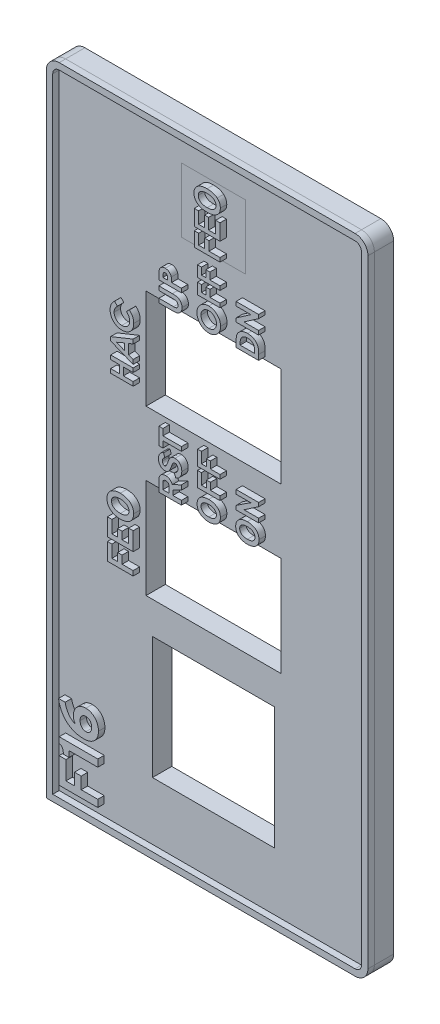
SolidWorks part; units mm, degrees
ref_plane "Front Plane" through (0, 0, 0) normal (1, 0, 0) x (0, 1, 0)
ref_plane "Top Plane" through (0, 0, 0) normal (0, 0, 1) x (0, 1, 0)
ref_plane "Right Plane" through (0, 0, 0) normal (0, 1, 0) x (-1, 0, 0)
sketch "Sketch1" plane through (0, 0, 0) normal (0, 0, 1) x (0, 1, 0)
  line L1 (2, 0) -> (98, 0)
  line L2 (0, 2) -> (0, 50)
  line L3 (0, 50) -> (98, 50)
  line L4 (100, 2) -> (100, 48)
  arc A0 (98, 50) -> (100, 48) centre (98, 48) cw
  arc A1 (98, 0) -> (100, 2) centre (98, 2) ccw
  arc A2 (2, 0) -> (0, 2) centre (2, 2) cw
  point P7 (100, 50)
  point P12 (0, 0)
  dimension "D3" = 2
  dimension "D1" = 100
  dimension "D2" = 50
extrude "Boss-Extrude1" add sketch "Sketch1" along normal blind 3
sketch "Sketch2" plane through (0, 0, 0) normal (0, 0, -1) x (1, 0, 0)
  line L0 (-25, 0) -> (-25, -100) construction
  line L9 (0, -2) -> (0, -98) construction
  line L10 (-35.5, -59.5) -> (-14.5, -59.5)
  line L11 (-50, 0) -> (-2, 0) construction
  line L12 (-2, -100) -> (-48, -100) construction
  line L13 (-35.5, -59.5) -> (-35.5, -75)
  line L14 (-34.5, -10) -> (-15.5, -10)
  line L15 (-34.5, -10) -> (-34.5, -29)
  line L16 (-34.5, -29) -> (-15.5, -29)
  line L17 (-15.5, -10) -> (-15.5, -29)
  line L18 (-34.5, -10) -> (-15.5, -29) construction
  line L19 (-34.5, -29) -> (-15.5, -10) construction
  line L20 (-35.5, -34) -> (-14.5, -34)
  line L21 (-35.5, -34) -> (-35.5, -49.5)
  line L22 (-35.5, -49.5) -> (-14.5, -49.5)
  line L23 (-14.5, -34) -> (-14.5, -49.5)
  line L24 (-35.5, -34) -> (-14.5, -49.5) construction
  line L25 (-35.5, -49.5) -> (-14.5, -34) construction
  line L26 (-35.5, -75) -> (-14.5, -75)
  line L27 (-14.5, -59.5) -> (-14.5, -75)
  line L28 (-35.5, -59.5) -> (-14.5, -75) construction
  line L29 (-35.5, -75) -> (-14.5, -59.5) construction
  line L31 (-30, -85) -> (-20, -85)
  line L32 (-30, -85) -> (-30, -95)
  line L33 (-30, -95) -> (-20, -95)
  line L34 (-20, -85) -> (-20, -95)
  line L35 (-30, -85) -> (-20, -95) construction
  line L36 (-30, -95) -> (-20, -85) construction
  point P0 (-25, -19.5)
  point P4 (-25, -67.25)
  point P17 (-25, -41.75)
  point P24 (-25, -90)
  dimension "D1" = 19
  dimension "D2" = 19
  dimension "D3" = 10
  dimension "D4" = 5
  dimension "D5" = 15.5
  dimension "D6" = 21
  dimension "D7" = 10
  dimension "D8" = 15.5
  dimension "D9" = 25
  dimension "D10" = 10
  dimension "D11" = 10
  dimension "D12" = 10
extrude "Cut-Extrude1" cut sketch "Sketch2" against normal blind 3
sketch "Sketch4" plane through (0, 0, 3) normal (0, 0, 1) x (1, 0, 0)
  line L18 (-23, 85) -> (-23, 95) construction
  line L23 (-42, 2) -> (-42, 25.5707) construction
  line L24 (-20, 85) -> (-30, 85) construction
  line L25 (-30, 95) -> (-20, 95) construction
  line L26 (-36.5, 34.1623) -> (-36.5, 48.9817) construction
  line L27 (-29, 49.5) -> (-29, 57.8291) construction
  line L28 (-23, 49.5) -> (-23, 58.6401) construction
  line L29 (-17, 49.5) -> (-17, 58.6401) construction
  line L30 (-14.5, 49.5) -> (-14.5, 34) construction
  line L31 (-20, 95) -> (-20, 85) construction
  line L32 (-35.5, 49.5) -> (-14.5, 49.5) construction
  line L33 (-14.5, 34) -> (-35.5, 34) construction
  line L34 (-35.5, 34) -> (-35.5, 49.5) construction
  line L35 (-14.5, 49.5) -> (-14.5, 34) construction
  line L36 (-35.5, 49.5) -> (-14.5, 49.5) construction
  line L37 (-14.5, 34) -> (-35.5, 34) construction
  line L38 (-35.5, 34) -> (-35.5, 49.5) construction
  line L39 (-25, 49.5) -> (-25, 34) construction
  line L40 (-25, 75) -> (-25, 59.5) construction
  line L41 (-35.5, 75) -> (-14.5, 75) construction
  line L42 (-14.5, 59.5) -> (-35.5, 59.5) construction
  line L43 (-29, 75) -> (-29, 97.2636) construction
  line L44 (-23, 75) -> (-23, 97.2636) construction
  line L45 (-17, 75) -> (-17, 97.2636) construction
  line L46 (-35.5, 59.5) -> (-35.5, 75) construction
  line L47 (-35.5, 59.5) -> (-35.5, 75) construction
  line L48 (-36.5, 59.5) -> (-36.5, 75) construction
  line L49 (-50, 0) -> (-2, 0) construction
  line L50 (-50, 98) -> (-50, 0) construction
  text T0 "<b>F16</b>" font "Overpass" height 6
  text T1 "<b>FEO</b>" font "Overpass" height 4
  text T2 "<b>RST</b>" font "Overpass" height 3.5
  text T3 "<b>OFF</b>" font "Overpass" height 3.5
  text T4 "<b>ON</b>" font "Overpass" height 3.5
  text T5 "<b>UP</b>"
  text T6 "<b>OFF</b>\r\n"
  text T7 "<b>DN</b>"
  text T8 "<b>HAC</b>"
  text T9 "FEO" font "Arial Narrow" height 4
  dimension "D3" = 6
  dimension "D4" = 6
  dimension "D5" = 1
  dimension "D6" = 2
  dimension "D7" = 2
  dimension "D8" = 6
  dimension "D9" = 6
  dimension "D2" = 3
  dimension "D11" = 2
  dimension "D12" = 8
  dimension "D10" = 1
sketch "Sketch5" plane through (0, 0, 0) normal (0, 0, -1) x (1, 0, 0)
  line L0 (-20, -95) -> (-20, -85) construction
  line L1 (-20, -95) -> (-20, -85)
  line L2 (-30, -95) -> (-20, -95) construction
  line L3 (-30, -85) -> (-30, -95) construction
  line L4 (-50, 0) -> (-50, -98)
  line L5 (-48, -100) -> (-2, -100)
  line L6 (0, -98) -> (0, -2)
  line L7 (-2, 0) -> (-50, 0)
  line L8 (-50, 0) -> (-50, -98)
  line L9 (-48, -100) -> (-2, -100)
  line L10 (0, -98) -> (0, -2)
  line L11 (-2, 0) -> (-50, 0)
  line L12 (-20, -85) -> (-30, -85) construction
  line L13 (-30, -95) -> (-20, -95)
  line L14 (-30, -85) -> (-30, -95)
  line L15 (-20, -85) -> (-30, -85)
  arc A3 (-50, -98) -> (-48, -100) centre (-48, -98) ccw
  arc A4 (-2, -100) -> (0, -98) centre (-2, -98) ccw
  arc A5 (0, -2) -> (-2, 0) centre (-2, -2) ccw
  arc A6 (-50, -98) -> (-48, -100) centre (-48, -98) ccw
  arc A7 (-2, -100) -> (0, -98) centre (-2, -98) ccw
  arc A8 (0, -2) -> (-2, 0) centre (-2, -2) ccw
  dimension "D1" = 0
extrude "Boss-Extrude6" add sketch "Sketch5" against normal up to surface (3 mm away) separate body contours L13 L1 L15 L14 up to face at (-25, 19.5, 3)
extrude "Boss-Extrude8" add sketch "Sketch4" along normal blind 1 separate body
sketch "Sketch6" plane through (0, 0, 3) normal (0, 0, 1) x (1, 0, 0)
  line L0 (-49, 98) -> (-49, 1)
  line L1 (-49, 1) -> (-2, 1)
  line L2 (-1, 2) -> (-1, 98)
  line L3 (-2, 99) -> (-48, 99)
  line L4 (-50, 98) -> (-50, 0)
  line L5 (-50, 0) -> (-2, 0)
  line L6 (0, 2) -> (0, 98)
  line L7 (-2, 100) -> (-48, 100)
  line L8 (-50, 98) -> (-50, 0)
  line L9 (-50, 0) -> (-2, 0)
  line L10 (0, 2) -> (0, 98)
  line L11 (-2, 100) -> (-48, 100)
  arc A0 (-2, 1) -> (-1, 2) centre (-2, 2) ccw
  arc A1 (-1, 98) -> (-2, 99) centre (-2, 98) ccw
  arc A2 (-48, 99) -> (-49, 98) centre (-48, 98) ccw
  arc A3 (-2, 0) -> (0, 2) centre (-2, 2) ccw
  arc A4 (0, 98) -> (-2, 100) centre (-2, 98) ccw
  arc A5 (-48, 100) -> (-50, 98) centre (-48, 98) ccw
  arc A6 (-2, 0) -> (0, 2) centre (-2, 2) ccw
  arc A7 (0, 98) -> (-2, 100) centre (-2, 98) ccw
  arc A8 (-48, 100) -> (-50, 98) centre (-48, 98) ccw
  dimension "D1" = 0
  dimension "D2" = 1
extrude "Boss-Extrude9" add sketch "Sketch6" along normal blind 1 separate body
